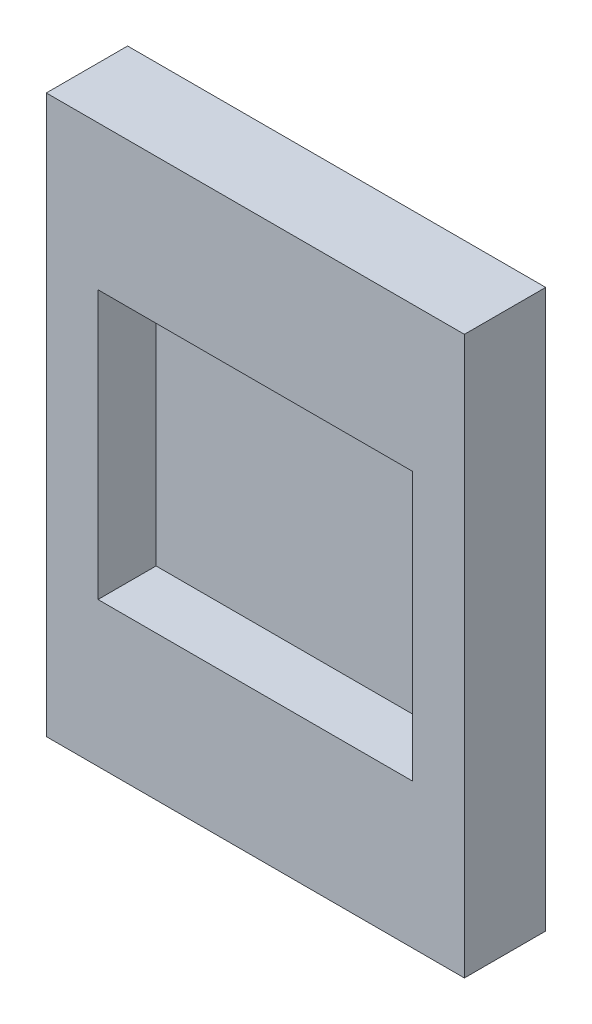
SolidWorks part; units mm, degrees
ref_plane "정면" through (0, 0, 0) normal (0, 0, 1) x (1, 0, 0)
ref_plane "윗면" through (0, 0, 0) normal (0, 1, 0) x (1, 0, 0)
ref_plane "우측면" through (0, 0, 0) normal (1, 0, 0) x (0, 0, -1)
sketch "스케치1" plane through (0, 0, 0) normal (0, 0, 1) x (1, 0, 0)
  line L1 (-9, -12) -> (9, -12)
  line L2 (-9, -12) -> (-9, 12)
  line L3 (-9, 12) -> (9, 12)
  line L4 (9, -12) -> (9, 12)
  line L5 (-9, -12) -> (9, 12) construction
  line L6 (-9, 12) -> (9, -12) construction
  point P0 (0, 0)
  dimension "D1" = 18
  dimension "D2" = 24
extrude "보스-돌출1" add sketch "스케치1" along normal blind 3.5
sketch "스케치2" plane through (0, 0, 3.5) normal (0, 0, 1) x (1, 0, 0)
  line L1 (-6.775, -5.775) -> (6.775, -5.775)
  line L2 (-6.775, -5.775) -> (-6.775, 5.775)
  line L3 (-6.775, 5.775) -> (6.775, 5.775)
  line L4 (6.775, -5.775) -> (6.775, 5.775)
  line L5 (-6.775, -5.775) -> (6.775, 5.775) construction
  line L6 (-6.775, 5.775) -> (6.775, -5.775) construction
  point P1 (0, 0)
  dimension "D1" = 13.55
  dimension "D2" = 11.55
extrude "컷-돌출1" cut sketch "스케치2" against normal blind 2.5
